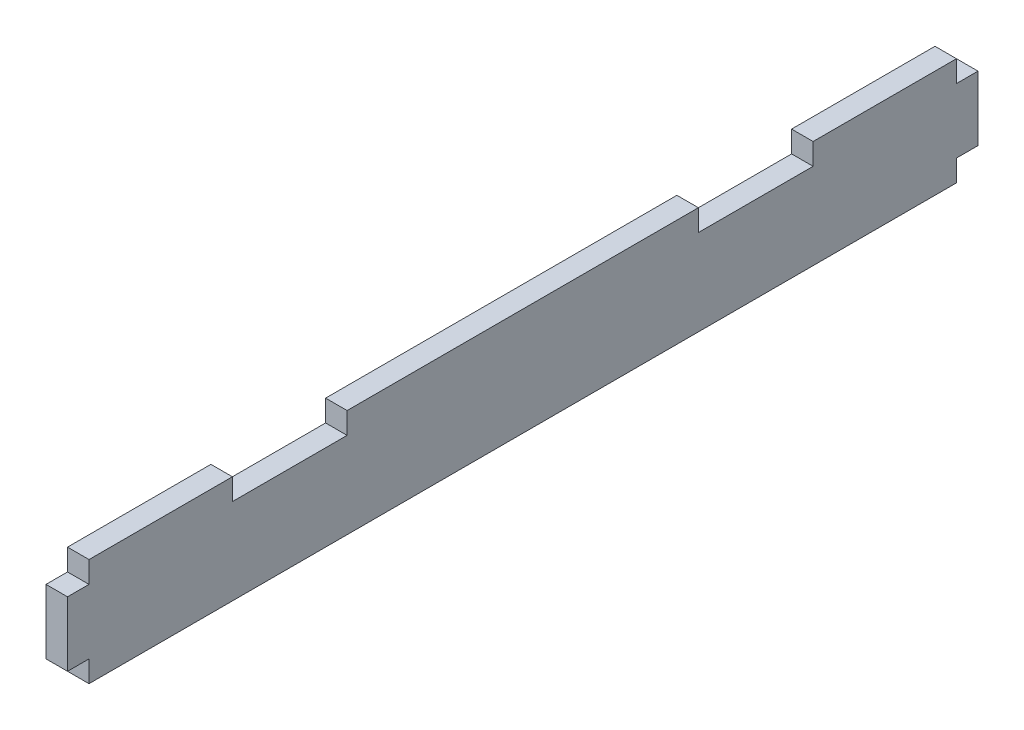
SolidWorks part; units mm, degrees
ref_plane "Front Plane" through (0, 0, 0) normal (0, 0, 1) x (1, 0, 0)
ref_plane "Top Plane" through (0, 0, 0) normal (0, 1, 0) x (1, 0, 0)
ref_plane "Right Plane" through (0, 0, 0) normal (1, 0, 0) x (0, 0, -1)
sketch "Sketch1" plane through (0, 0, 0) normal (1, 0, 0) x (0, 0, -1)
  line L1 (0, 0) -> (121, 0)
  line L2 (0, 0) -> (0, 15)
  line L3 (0, 15) -> (121, 15)
  line L4 (121, 0) -> (121, 15)
  line L5 (0, 12) -> (-3, 12)
  line L6 (0, 12) -> (0, 3)
  line L7 (0, 3) -> (-3, 3)
  line L8 (-3, 12) -> (-3, 3)
  line L9 (121, 12) -> (124, 12)
  line L10 (121, 12) -> (121, 3)
  line L11 (121, 3) -> (124, 3)
  line L12 (124, 12) -> (124, 3)
  line L13 (20, 15) -> (36, 15)
  line L14 (20, 15) -> (20, 12)
  line L15 (20, 12) -> (36, 12)
  line L16 (36, 15) -> (36, 12)
  line L17 (101, 15) -> (85, 15)
  line L18 (101, 15) -> (101, 12)
  line L19 (101, 12) -> (85, 12)
  line L20 (85, 15) -> (85, 12)
  dimension "D1" = 15
  dimension "D2" = 121
  dimension "D3" = 3
  dimension "D4" = 3
  dimension "D5" = 3
  dimension "D6" = 3
  dimension "D7" = 3
  dimension "D8" = 3
  dimension "D9" = 3
  dimension "D10" = 16
  dimension "D11" = 3
  dimension "D12" = 16
  dimension "D13" = 20
  dimension "D14" = 20
extrude "Boss-Extrude1" add sketch "Sketch1" along normal blind 3 contours L20 L3 L16 L15 L14 L2 L1 L4 L18 L19 | L5 L8 L7 L2 | L12 L9 L4 L11
